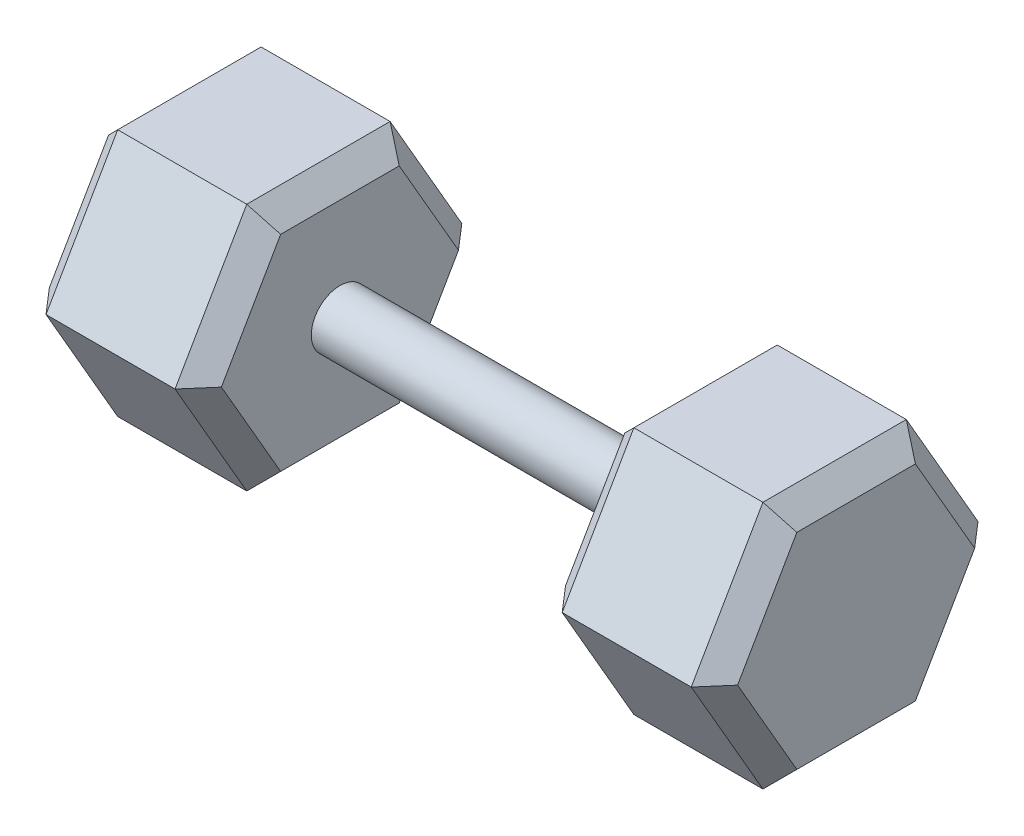
SolidWorks part; units mm, degrees
ref_plane "Front" through (0, 0, 0) normal (0, 0, 1) x (1, 0, 0)
ref_plane "Top" through (0, 0, 0) normal (0, 1, 0) x (1, 0, 0)
ref_plane "Right" through (0, 0, 0) normal (1, 0, 0) x (0, 0, -1)
sketch "Sketch1" plane through (0, 0, 0) normal (1, 0, 0) x (0, 0, -1)
  line L1 (63.5, 0) -> (31.75, 54.9926)
  line L2 (31.75, 54.9926) -> (-31.75, 54.9926)
  line L3 (-31.75, 54.9926) -> (-63.5, 0)
  line L4 (-63.5, 0) -> (-31.75, -54.9926)
  line L5 (-31.75, -54.9926) -> (31.75, -54.9926)
  line L6 (31.75, -54.9926) -> (63.5, 0)
  circle A0 centre (0, 0) radius 54.9926 construction
  dimension "D1" = 127
extrude "Base-Extrude" add sketch "Sketch1" along normal blind 76.2
chamfer "Chamfer1" distance 9.525 angle 45 12 edges at (76.2, 54.9926, 0) (76.2, 27.4963, 47.625) (76.2, -27.4963, 47.625) (76.2, -54.9926, 0) (76.2, -27.4963, -47.625) (0, -54.9926, 0) (0, -27.4963, 47.625) (0, 27.4963, 47.625) (76.2, 27.4963, -47.625) (0, 54.9926, 0) (0, 27.4963, -47.625) (0, -27.4963, -47.625)
sketch "Sketch2" plane through (76.2, 0, 0) normal (1, 0, 0) x (0, 0, -1)
  circle A0 centre (0, 0) radius 12.6913
extrude "Boss-Extrude1" add sketch "Sketch2" along normal blind 76.2
mirror "Mirror All1" about plane through (152.4, 0, 0) normal (1, 0, 0) of bodies 102
